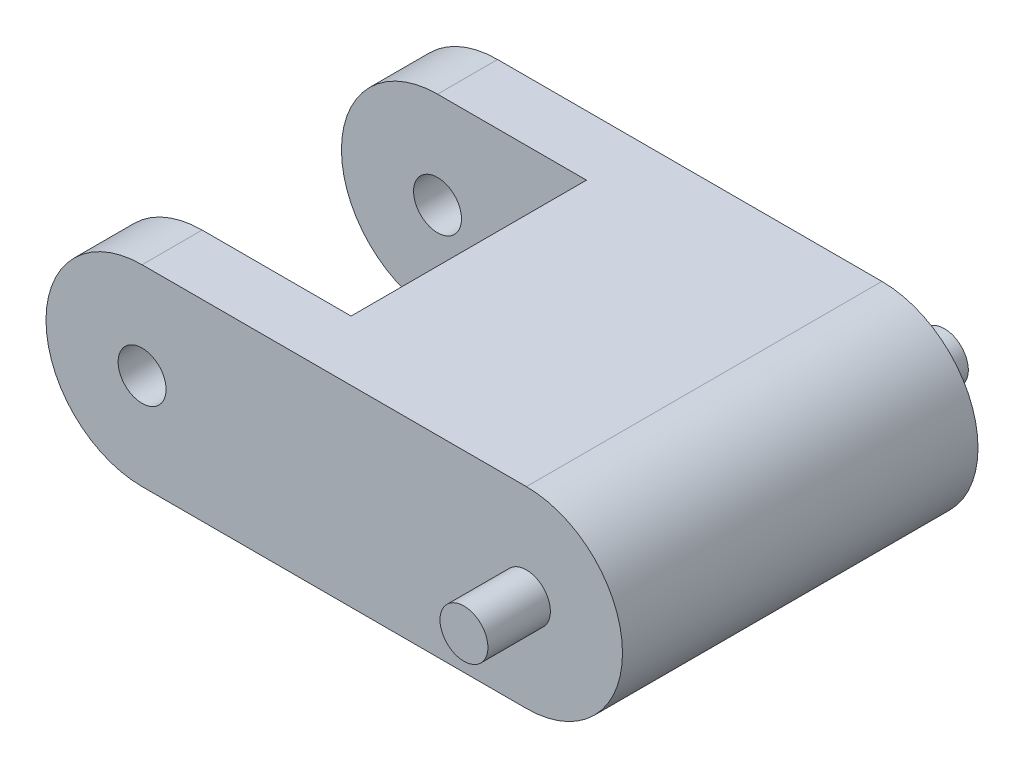
SolidWorks part; units mm, degrees
ref_plane "Alzado" through (0, 0, 0) normal (0, 0, 1) x (1, 0, 0)
ref_plane "Planta" through (0, 0, 0) normal (0, 1, 0) x (1, 0, 0)
ref_plane "Vista lateral" through (0, 0, 0) normal (1, 0, 0) x (0, 0, -1)
sketch "Croquis1" plane through (0, 0, 0) normal (0, 0, 1) x (1, 0, 0)
  line L0 (0, 40) -> (160, 40)
  line L1 (0, -40) -> (160, -40)
  line L2 (160, -40) -> (160, 0) construction
  line L3 (160, 0) -> (200, 0) construction
  line L4 (200, 0) -> (160, 0) construction
  arc A0 (0, 40) -> (0, -40) centre (0, 0) ccw
  arc A1 (160, -40) -> (160, 40) centre (160, 0) ccw
  circle A2 centre (0, 0) radius 9.977
extrude "Saliente-Extruir9" add sketch "Croquis1" along normal blind 148
sketch "Croquis8" plane through (0, 0, 0) normal (0, 0, -1) x (-1, 0, 0)
  circle A0 centre (-160, 0) radius 9.977
extrude "Saliente-Extruir10" add sketch "Croquis8" along normal blind 26 and the other way blind 174
sketch "Croquis9" plane through (0, 40, 0) normal (0, 1, 0) x (1, 0, 0)
  line L1 (62.0053, -25) -> (-52.3837, -25)
  line L2 (62.0053, -25) -> (62.0053, -123)
  line L3 (62.0053, -123) -> (-52.3837, -123)
  line L4 (-52.3837, -25) -> (-52.3837, -123)
  dimension "D1" = 25
  dimension "D2" = 25
  dimension "D3" = 98
extrude "Cortar-Extruir2" cut sketch "Croquis9" against normal blind 131
